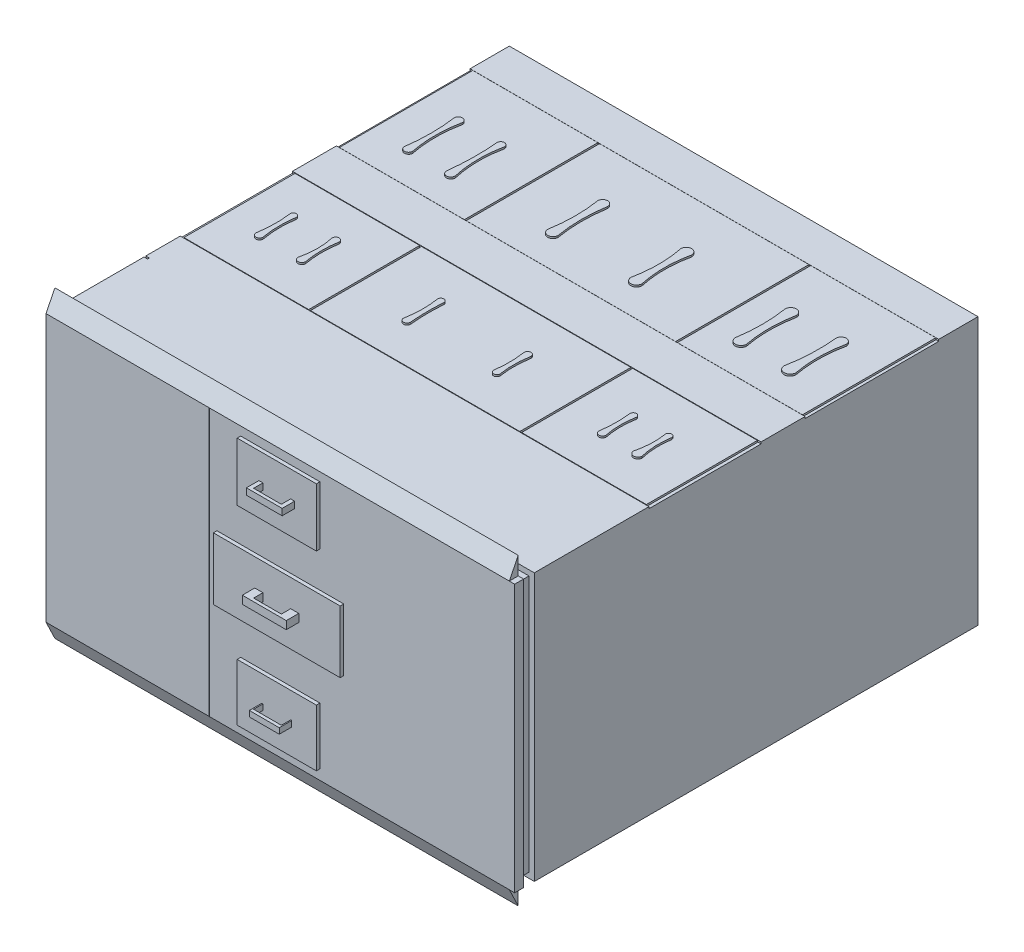
SolidWorks part; units mm, degrees
ref_plane "Alzado" through (0, 0, 0) normal (0, 0, 1) x (1, 0, 0)
ref_plane "Planta" through (0, 0, 0) normal (0, 1, 0) x (1, 0, 0)
ref_plane "Vista lateral" through (0, 0, 0) normal (1, 0, 0) x (0, 0, -1)
sketch "Croquis1" plane through (0, 0, 0) normal (0, 0, 1) x (1, 0, 0)
  line L1 (-1315, -750) -> (1315, -750)
  line L2 (-1315, -750) -> (-1315, 750)
  line L3 (-1315, 750) -> (1315, 750)
  line L4 (1315, -750) -> (1315, 750)
  line L5 (-1315, -750) -> (1315, 750) construction
  line L6 (-1315, 750) -> (1315, -750) construction
  point P0 (0, 0)
  dimension "D1" = 2630
  dimension "D2" = 1500
extrude "Saliente-Extruir1" add sketch "Croquis1" along normal blind 2600
sketch "Croquis2" plane through (-1315, 0, 0) normal (-1, 0, 0) x (0, 0, 1)
  line L0 (2600, 750) -> (0, 750) construction
  line L1 (2000, 600) -> (200, 600)
  line L2 (2000, 600) -> (2000, -100)
  line L3 (2000, -100) -> (200, -100)
  line L4 (200, 600) -> (200, -100)
  line L5 (2000, 600) -> (200, -100) construction
  line L6 (2000, -100) -> (200, 600) construction
  line L7 (0, 750) -> (0, -750) construction
  line L9 (200.2352, 599.7238) -> (1999.7648, 599.7238)
  line L10 (200.2352, 599.7238) -> (200.2352, -99.7238)
  line L11 (200.2352, -99.7238) -> (1999.7648, -99.7238)
  line L12 (1999.7648, 599.7238) -> (1999.7648, -99.7238)
  line L13 (200.2352, 599.7238) -> (1999.7648, -99.7238) construction
  line L14 (200.2352, -99.7238) -> (1999.7648, 599.7238) construction
  point P0 (1100, 250)
  point P9 (1100, 250)
  dimension "D1" = 700
  dimension "D2" = 150
  dimension "D3" = 200
  dimension "D4" = 1800
extrude "Cortar-Extruir1" cut sketch "Croquis2" against normal blind 5
sketch "Croquis3" plane through (-1315, 0, 0) normal (-1, 0, 0) x (0, 0, 1)
  line L0 (1319.1367, 475.2666) -> (1319.1367, 65.2031) construction
  text T0 "KVA" font "Century Gothic" height in points 500
extrude "Saliente-Extruir2" add sketch "Croquis3" along normal blind 10
sketch "Croquis4" plane through (-1315, 0, 0) normal (-1, 0, 0) x (0, 0, 1)
  line L1 (1526.4759, -439.6523) -> (1976.8806, -439.6523)
  line L2 (1526.4759, -439.6523) -> (1526.4759, -764.9446)
  line L3 (1526.4759, -764.9446) -> (1976.8806, -764.9446)
  line L4 (1976.8806, -439.6523) -> (1976.8806, -764.9446)
  line L5 (1526.4759, -439.6523) -> (1976.8806, -764.9446) construction
  line L6 (1526.4759, -764.9446) -> (1976.8806, -439.6523) construction
  line L7 (1526.7662, -439.8619) -> (1976.5903, -439.8619)
  line L8 (1526.7662, -439.8619) -> (1526.7662, -764.7349)
  line L9 (1526.7662, -764.7349) -> (1976.5903, -764.7349)
  line L10 (1976.5903, -439.8619) -> (1976.5903, -764.7349)
  line L11 (1526.7662, -439.8619) -> (1976.5903, -764.7349) construction
  line L12 (1526.7662, -764.7349) -> (1976.5903, -439.8619) construction
  point P0 (1751.6783, -602.2984)
  point P5 (1751.6783, -602.2984)
extrude "Cortar-Extruir2" cut sketch "Croquis4" against normal blind 5
sketch "Croquis5" plane through (-1315, 0, 0) normal (-1, 0, 0) x (0, 0, 1)
  arc A0 (1780.3382, -740.7629) -> (1780.3382, -710.8196) centre (1780.3382, -725.7913) ccw
  arc A1 (1780.3382, -710.8196) -> (1648.3179, -710.8196) centre (1714.3281, 64.5749) cw
  arc A2 (1780.3382, -740.7629) -> (1648.3179, -740.7629) centre (1714.3281, -1706.2715) ccw
  arc A3 (1648.3179, -740.7629) -> (1648.3179, -710.8196) centre (1651.5059, -725.7913) cw
extrude "Saliente-Extruir3" add sketch "Croquis5" along normal blind 130
sketch "Croquis6" plane through (-1315, 0, 0) normal (-1, 0, 0) x (0, 0, 1)
  line L1 (2012.3737, -428.6401) -> (1976.0048, -428.6401)
  line L2 (2012.3737, -428.6401) -> (2012.3737, -783.2373)
  line L3 (2012.3737, -783.2373) -> (1976.0048, -783.2373)
  line L4 (1976.0048, -428.6401) -> (1976.0048, -783.2373)
  line L5 (2012.3737, -428.6401) -> (1976.0048, -783.2373) construction
  line L6 (2012.3737, -783.2373) -> (1976.0048, -428.6401) construction
  point P0 (1994.1892, -605.9387)
extrude "Saliente-Extruir4" add sketch "Croquis6" along normal blind 10
sketch "Croquis7" plane through (-1315, 0, 0) normal (-1, 0, 0) x (0, 0, 1)
  line L0 (2002.8088, -428.6401) -> (2002.8088, -392.561)
  line L1 (2012.3737, -428.6401) -> (1976.0048, -428.6401) construction
  line L2 (2002.8088, -392.561) -> (1981.5113, -392.561)
  line L3 (1981.5113, -392.561) -> (1981.5113, -403.6193)
  line L4 (1981.5113, -428.6401) -> (1981.5113, -403.6193)
  line L6 (2002.8088, -783.2373) -> (2002.8088, -750)
  line L7 (1976.0048, -783.2373) -> (2012.3737, -783.2373) construction
  line L8 (2600, -750) -> (2012.3737, -750) construction
  line L9 (2002.8088, -750) -> (1981.5113, -750)
  line L10 (1981.5113, -750) -> (1981.5113, -783.2373)
  line L11 (1981.5113, -783.2373) -> (2002.8088, -783.2373)
  line L12 (1981.5113, -428.6401) -> (2002.8088, -428.6401)
  line L14 (2002.8088, -783.2373) -> (2002.6702, -783.1658)
extrude "Saliente-Extruir5" add sketch "Croquis7" along normal blind 10
sketch "Croquis8" plane through (-1315, 0, 0) normal (-1, 0, 0) x (0, 0, 1)
  arc A0 (1260.1406, -2.5348) -> (1259.4668, 20.6791) centre (1260.4672, 9.0914) ccw
  arc A1 (1260.1406, -2.5348) -> (1056.2677, -15.1971) centre (1241.402, -1348.4194) ccw
  arc A2 (1259.4668, 20.6791) -> (1056.2677, 37.0054) centre (1224.0968, 853.1435) cw
  arc A3 (1056.2677, 37.0054) -> (1056.2677, -15.1971) centre (1056.2677, 10.9041) ccw
extrude "Saliente-Extruir6" add sketch "Croquis8" along normal blind 10
sketch "Croquis9" plane through (-1315, 0, 0) normal (-1, 0, 0) x (0, 0, 1)
  line L1 (1985.9589, 369.0843) -> (1802.2688, 369.0843)
  line L2 (1985.9589, 369.0843) -> (1985.9589, 242.2506)
  line L3 (1985.9589, 242.2506) -> (1802.2688, 242.2506)
  line L4 (1802.2688, 369.0843) -> (1802.2688, 242.2506)
  line L5 (1985.9589, 369.0843) -> (1802.2688, 242.2506) construction
  line L6 (1985.9589, 242.2506) -> (1802.2688, 369.0843) construction
  line L7 (1803.3097, 367.3482) -> (1984.918, 367.3482)
  line L8 (1803.3097, 367.3482) -> (1803.3097, 243.9867)
  line L9 (1803.3097, 243.9867) -> (1984.918, 243.9867)
  line L10 (1984.918, 367.3482) -> (1984.918, 243.9867)
  line L11 (1803.3097, 367.3482) -> (1984.918, 243.9867) construction
  line L12 (1803.3097, 243.9867) -> (1984.918, 367.3482) construction
  point P0 (1894.1138, 305.6675)
  point P5 (1894.1138, 305.6675)
extrude "Cortar-Extruir3" cut sketch "Croquis9" against normal blind 5
sketch "Croquis10" plane through (-1315, 0, 0) normal (-1, 0, 0) x (0, 0, 1)
  line L1 (2600, 750) -> (0, 750) construction
  line L2 (2050, 750) -> (2050, -750)
  line L3 (2600, -750) -> (2012.3737, -750) construction
  line L4 (2050, -750) -> (2040, -750)
  line L5 (2040, -750) -> (2040, 750)
  line L6 (2040, 750) -> (2050, 750)
  dimension "D2" = 10
extrude "Cortar-Extruir4" cut sketch "Croquis10" against normal blind 20
sketch "Croquis11" plane through (0, -750, 0) normal (0, -1, 0) x (1, 0, 0)
  line L0 (-1315, 2600) -> (-1315, 2050)
  line L1 (-1315, 2600) -> (-1315, 2050) construction
  line L2 (-1315, 2050) -> (1315, 2050)
  line L3 (1315, 2600) -> (1315, 0) construction
  line L4 (1315, 2050) -> (1309.7781, 2050)
  line L5 (1309.7781, 2050) -> (1309.7781, 2040)
  line L6 (1309.7781, 2040) -> (-1341.4375, 2040)
  line L7 (-1341.4375, 2040) -> (-1341.4375, 2050)
  line L8 (-1341.4375, 2050) -> (-1315, 2050)
  line M6 (-1295, 2050) -> (-1295, 2040)
  line M14 (1315, 0) -> (1315, 2600)
  dimension "D1" = 550
  dimension "D2" = 10
extrude "Cortar-Extruir5" cut sketch "Croquis11" against normal blind 20 contours L6 L2 M14 M6
sketch "Croquis14" plane through (-1315, 0, 0) normal (-1, 0, 0) x (0, 0, 1)
  line L0 (2370.2413, 341.8092) -> (2353.0065, 332.4084)
  line L1 (2353.0065, 332.4084) -> (2310.7029, 360.6108)
  line L2 (2310.7029, 360.6108) -> (2291.9013, 332.4084)
  line L3 (2291.9013, 332.4084) -> (2249.5977, 360.6108)
  line L4 (2249.5977, 360.6108) -> (2233.9297, 337.1088)
  line L5 (2233.9297, 337.1088) -> (2214.5255, 308.0025)
  line L6 (2214.5255, 308.0025) -> (2241.7637, 313.4502)
  line L10 (2241.7637, 313.4502) -> (2241.7637, 294.0219)
  line L11 (2241.7637, 294.0219) -> (2282.5005, 313.4502)
  line L12 (2282.5005, 313.4502) -> (2259.9673, 274.409)
  line L13 (2259.9673, 274.409) -> (2313.8766, 308.0025)
  line L14 (2313.8766, 308.0025) -> (2305.6973, 282.9601)
  line L15 (2305.6973, 282.9601) -> (2386.4898, 323.9697)
  line L16 (2386.4898, 323.9697) -> (2370.2413, 341.8092)
  point P0 (2276.2984, 324.5929)
extrude "Saliente-Extruir7" add sketch "Croquis14" along normal blind 20
sketch "Croquis15" plane through (-1315, 0, 0) normal (-1, 0, 0) x (0, 0, 1)
  line L1 (2440.381, 319.4871) -> (2183.8004, 467.6239)
  line L2 (2183.8004, 467.6239) -> (2183.8004, 171.3502)
  line L3 (2183.8004, 171.3502) -> (2440.381, 319.4871)
  circle A0 centre (2269.3272, 319.4871) radius 85.5269 construction
extrude "Saliente-Extruir8" add sketch "Croquis15" along normal blind 10
sketch "Croquis16" plane through (-1315, 0, 0) normal (-1, 0, 0) x (0, 0, 1)
  line L1 (2600, 750) -> (2050, 750) construction
  line L2 (2550, 750) -> (2490, 750)
  line L3 (2490, 750) -> (2490, -750)
  line L4 (2600, -750) -> (2050, -750) construction
  line L5 (2490, -750) -> (2550, -750)
  line L6 (2550, -750) -> (2550, 750)
  dimension "D2" = 60
extrude "Cortar-Extruir8" cut sketch "Croquis16" against normal blind 30
sketch "Croquis17" plane through (0, -750, 0) normal (0, -1, 0) x (1, 0, 0)
  line L0 (1388.3737, 2490) -> (-1371.915, 2490)
  line L1 (1388.3737, 2550) -> (1388.3737, 2490)
  line L2 (-1371.915, 2490) -> (-1371.915, 2550)
  line L3 (-1371.915, 2550) -> (1388.3737, 2550)
  dimension "D1" = 60
extrude "Cortar-Extruir9" cut sketch "Croquis17" against normal blind 30
sketch "Croquis18" plane through (1315, 0, 0) normal (1, 0, 0) x (0, 0, -1)
  line L0 (-2550, -917.8528) -> (-2550, 835.2908)
  line L3 (-2550, 835.2908) -> (-2490, 835.2908)
  line L4 (-2490, 835.2908) -> (-2490, -917.8528)
  line L5 (-2490, -917.8528) -> (-2550, -917.8528)
  dimension "D1" = 60
extrude "Cortar-Extruir10" cut sketch "Croquis18" against normal blind 30
sketch "Croquis19" plane through (0, 750, 0) normal (0, 1, 0) x (1, 0, 0)
  line L1 (1315, -2550) -> (-1411.6841, -2550)
  line L2 (-1411.6841, -2550) -> (-1411.6841, -2490)
  line L3 (-1411.6841, -2490) -> (1341.505, -2490)
  line L4 (1341.505, -2490) -> (1341.505, -2550)
  line L5 (1341.505, -2550) -> (1315, -2550)
extrude "Cortar-Extruir11" cut sketch "Croquis19" against normal blind 30
sketch "Croquis20" plane through (-1315, 0, 0) normal (-1, 0, 0) x (0, 0, 1)
  line L0 (2550, -750) -> (2550, -853.7683)
  line L1 (2550, -853.7683) -> (2600, -750)
  line L2 (2550, 750) -> (2550, 850.1214)
  line L3 (2550, 850.1214) -> (2600, 750)
  line L4 (2600, 750) -> (2550, 750)
  line L5 (2550, -750) -> (2600, -750)
extrude "Saliente-Extruir9" add sketch "Croquis20" against normal blind 2600
sketch "Croquis28" plane through (0, 750, 0) normal (0, 1, 0) x (1, 0, 0)
  line L0 (1315, -1846.4807) -> (-1315, -1846.4807)
  line L1 (1315, -2490) -> (1315, 0) construction
  line L2 (-1315, -2040) -> (-1315, 0) construction
  line L3 (1315, -1846.4807) -> (1315, -1217.335)
  line L4 (1315, -1217.335) -> (-1315, -1217.335)
  line L5 (-1315, -1217.335) -> (-1315, -1846.4807)
  line L7 (1297.5126, -1220.2763) -> (-1297.5126, -1220.2763)
  line L8 (1297.5126, -1220.2763) -> (1297.5126, -1843.5394)
  line L9 (1297.5126, -1843.5394) -> (-1297.5126, -1843.5394)
  line L10 (-1297.5126, -1220.2763) -> (-1297.5126, -1843.5394)
  line L11 (1297.5126, -1220.2763) -> (-1297.5126, -1843.5394) construction
  line L12 (1297.5126, -1843.5394) -> (-1297.5126, -1220.2763) construction
  point P6 (0, -1531.9079)
extrude "Cortar-Extruir18" cut sketch "Croquis28" against normal blind 10
sketch "Croquis29" plane through (0, 750, 0) normal (0, 1, 0) x (1, 0, 0)
  line L0 (-597.5126, -1531.9079) -> (-597.5126, -1843.5394)
  line L4 (597.5126, -1843.5394) -> (597.5126, -1220.2763)
  line L7 (597.5126, -1220.2763) -> (587.5126, -1220.2763)
  line L8 (1297.5126, -1220.2763) -> (-1297.5126, -1220.2763) construction
  line L9 (1297.5126, -1220.2763) -> (-1297.5126, -1220.2763) construction
  line L10 (587.5126, -1220.2763) -> (587.5126, -1843.5394)
  line L11 (-1297.5126, -1843.5394) -> (1297.5126, -1843.5394) construction
  line L12 (587.5126, -1843.5394) -> (597.5126, -1843.5394)
  line L13 (-597.5126, -1843.5394) -> (-587.5126, -1843.5394)
  line L14 (-587.5126, -1843.5394) -> (-587.5126, -1220.2763)
  line L15 (-587.5126, -1220.2763) -> (-597.5126, -1220.2763)
  line L16 (-597.5126, -1220.2763) -> (-597.5126, -1531.9079)
  dimension "D1" = 10
  dimension "D3" = 10
extrude "Cortar-Extruir19" cut sketch "Croquis29" against normal blind 10
sketch "Croquis30" plane through (0, 750, 0) normal (0, 1, 0) x (1, 0, 0)
  line L0 (1315, -220.2763) -> (1315, -970.2763)
  line L1 (1315, -1217.335) -> (1315, 0) construction
  line L2 (1297.5126, -1220.2763) -> (597.5126, -1220.2763) construction
  line L3 (1315, -970.2763) -> (1003.7101, -970.2763)
  line L4 (-1315, -970.2763) -> (-1315, -220.2763)
  line L5 (-1315, -1217.335) -> (-1315, 0) construction
  line L6 (-1315, -220.2763) -> (1315, -220.2763)
  line L8 (-1315, -970.2763) -> (1003.7101, -970.2763)
  line L9 (1299.2276, -221.062) -> (-1299.2276, -221.062)
  line L10 (1299.2276, -221.062) -> (1299.2276, -969.4906)
  line L11 (1299.2276, -969.4906) -> (-1299.2276, -969.4906)
  line L12 (-1299.2276, -221.062) -> (-1299.2276, -969.4906)
  line L13 (1299.2276, -221.062) -> (-1299.2276, -969.4906) construction
  line L14 (1299.2276, -969.4906) -> (-1299.2276, -221.062) construction
  point P11 (0, -595.2763)
  dimension "D1" = 750
  dimension "D2" = 250
extrude "Cortar-Extruir20" cut sketch "Croquis30" against normal blind 10
sketch "Croquis31" plane through (0, 750, 0) normal (0, 1, 0) x (1, 0, 0)
  line L0 (587.5126, -969.4906) -> (587.5126, -221.062)
  line L1 (-1299.2276, -969.4906) -> (1299.2276, -969.4906) construction
  line L2 (1299.2276, -221.062) -> (-1299.2276, -221.062) construction
  line L3 (587.5126, -221.062) -> (597.5126, -221.062)
  line L4 (597.5126, -221.062) -> (597.5126, -969.4906)
  line L5 (-1299.2276, -969.4906) -> (1299.2276, -969.4906) construction
  line L6 (597.5126, -969.4906) -> (587.5126, -969.4906)
  line L7 (-587.5126, -969.4906) -> (-587.5126, -221.062)
  line L8 (-587.5126, -221.062) -> (-597.5126, -221.062)
  line L9 (1299.2276, -221.062) -> (-1299.2276, -221.062) construction
  line L10 (-597.5126, -221.062) -> (-597.5126, -969.4906)
  line L11 (-597.5126, -969.4906) -> (-587.5126, -969.4906)
  dimension "D1" = 10
  dimension "D2" = 10
extrude "Cortar-Extruir21" cut sketch "Croquis31" against normal blind 10
sketch "Croquis32" plane through (0, 750, 0) normal (0, 1, 0) x (1, 0, 0)
  arc A0 (226.1322, -1629.2485) -> (262.3012, -1629.2485) centre (244.2167, -1629.2485) ccw
  arc A1 (-279.5439, -1629.2485) -> (-240.2668, -1629.2485) centre (-259.9054, -1629.2485) ccw
  arc A2 (-242.3401, -1439.544) -> (-277.4706, -1439.544) centre (-259.9054, -1439.544) ccw
  arc A3 (263.5384, -1457.1092) -> (224.8949, -1457.1092) centre (244.2167, -1457.1092) ccw
  arc A4 (263.5384, -1457.1092) -> (262.3012, -1629.2485) centre (777.7885, -1546.8795) ccw
  arc A5 (224.8949, -1457.1092) -> (226.1322, -1629.2485) centre (-345.2759, -1547.2814) cw
  arc A6 (-240.2668, -1629.2485) -> (-242.3401, -1439.544) centre (860.3622, -1522.3561) cw
  arc A7 (-279.5439, -1629.2485) -> (-277.4706, -1439.544) centre (-830.4924, -1528.3636) ccw
  arc A8 (-871.2729, -1629.2485) -> (-828.94, -1629.2485) centre (-850.1064, -1629.2485) ccw
  arc A9 (-830.4492, -1439.544) -> (-869.7637, -1439.544) centre (-850.1064, -1439.544) ccw
  arc A10 (-1071.1318, -1444.6629) -> (-1104.8565, -1444.2543) centre (-1087.9346, -1439.544) ccw
  arc A11 (-1108.2578, -1629.2485) -> (-1067.6114, -1629.2485) centre (-1087.9346, -1629.2485) ccw
  arc A12 (816.9987, -1629.2485) -> (857.2101, -1629.2485) centre (837.1044, -1629.2485) ccw
  arc A13 (1011.5094, -1629.2485) -> (1060.1358, -1629.2485) centre (1035.8226, -1629.2485) ccw
  arc A14 (1053.2252, -1457.1092) -> (1018.42, -1457.1092) centre (1035.8226, -1457.1092) ccw
  arc A15 (855.1846, -1457.1092) -> (819.0242, -1457.1092) centre (837.1044, -1457.1092) ccw
  arc A16 (1053.2252, -1457.1092) -> (1060.1358, -1629.2485) centre (1486.1051, -1525.9395) ccw
  arc A17 (1018.42, -1457.1092) -> (1011.5094, -1629.2485) centre (598.9406, -1526.4774) cw
  arc A18 (857.2101, -1629.2485) -> (855.1846, -1457.1092) centre (1297.0728, -1537.9912) cw
  arc A19 (819.0242, -1457.1092) -> (816.9987, -1629.2485) centre (191.1998, -1535.8034) cw
  arc A20 (-828.94, -1629.2485) -> (-830.4492, -1439.544) centre (-292.9516, -1530.1262) cw
  arc A21 (-871.2729, -1629.2485) -> (-869.7637, -1439.544) centre (-1280.813, -1531.1322) ccw
  arc A22 (-1067.6114, -1629.2485) -> (-1071.1318, -1444.6629) centre (-506.0515, -1526.212) cw
  arc A23 (-1108.2578, -1629.2485) -> (-1104.8565, -1444.2543) centre (-1717.4157, -1525.52) ccw
  arc A24 (-1110.9413, -792.7224) -> (-1064.9279, -792.7224) centre (-1087.9346, -792.7224) ccw
  arc A25 (-1065.0376, -513.457) -> (-1110.8317, -513.457) centre (-1087.9346, -513.457) ccw
  arc A26 (-874.7473, -792.7224) -> (-825.4655, -792.7224) centre (-850.1064, -792.7224) ccw
  arc A27 (-829.2909, -513.457) -> (-870.9219, -513.457) centre (-850.1064, -513.457) ccw
  arc A28 (-306.7551, -792.7224) -> (-248.1861, -792.7224) centre (-277.4706, -792.7224) ccw
  arc A29 (-249.5291, -513.457) -> (-305.412, -513.457) centre (-277.4706, -513.457) ccw
  arc A30 (160.1374, -792.7224) -> (222.2622, -792.7224) centre (191.1998, -792.7224) ccw
  arc A31 (221.5603, -513.457) -> (160.8393, -513.457) centre (191.1998, -513.457) ccw
  arc A32 (746.2642, -792.7224) -> (809.3128, -792.7224) centre (777.7885, -792.7224) ccw
  arc A33 (1019.7171, -792.7224) -> (1086.7333, -792.7224) centre (1053.2252, -792.7224) ccw
  arc A34 (1089.2252, -513.457) -> (1031.0464, -513.457) centre (1060.1358, -513.457) ccw
  arc A35 (809.4047, -513.457) -> (746.1723, -513.457) centre (777.7885, -513.457) ccw
  arc A36 (1089.2252, -513.457) -> (1086.7333, -792.7224) centre (1783.923, -659.2997) ccw
  arc A37 (1019.7171, -792.7224) -> (1031.0464, -513.457) centre (85.1894, -614.9479) ccw
  arc A38 (809.3128, -792.7224) -> (809.4047, -513.457) centre (1521.75, -653.324) cw
  arc A39 (746.2642, -792.7224) -> (746.1723, -513.457) centre (-132.8526, -653.3789) ccw
  arc A40 (222.2622, -792.7224) -> (221.5603, -513.457) centre (859.9671, -651.4861) cw
  arc A41 (160.1374, -792.7224) -> (160.8393, -513.457) centre (-524.7998, -651.3674) ccw
  arc A42 (-248.1861, -792.7224) -> (-249.5291, -513.457) centre (589.4791, -649.0578) cw
  arc A43 (-306.7551, -792.7224) -> (-305.412, -513.457) centre (-1147.1072, -649.0449) ccw
  arc A44 (-825.4655, -792.7224) -> (-829.2909, -513.457) centre (-190.2916, -644.3628) cw
  arc A45 (-874.7473, -792.7224) -> (-870.9219, -513.457) centre (-2154.9057, -635.5278) ccw
  arc A46 (-1064.9279, -792.7224) -> (-1065.0376, -513.457) centre (-368.6066, -652.8163) cw
  arc A47 (-1110.9413, -792.7224) -> (-1110.8317, -513.457) centre (-2113.3391, -652.6961) ccw
extrude "Saliente-Extruir11" add sketch "Croquis32" along normal blind 10
sketch "Croquis34" plane through (-1315, 0, 0) normal (-1, 0, 0) x (0, 0, 1)
  line L1 (1526.7662, -439.8619) -> (1976.0048, -439.8619)
  line L2 (1526.7662, -439.8619) -> (1526.7662, -750)
  line L3 (1526.7662, -750) -> (1976.0048, -750)
  line L4 (1976.0048, -439.8619) -> (1976.0048, -750)
  line L5 (1526.7662, -439.8619) -> (1976.0048, -750) construction
  line L6 (1526.7662, -750) -> (1976.0048, -439.8619) construction
  point P0 (1751.3855, -594.931)
extrude "Saliente-Extruir14" add sketch "Croquis34" along normal blind 120
sketch "Croquis35" plane through (0, 0, 2600) normal (0, 0, 1) x (1, 0, 0)
  line L1 (-400, 0) -> (-400, -56.3996)
  line L2 (397.6045, 797.864) -> (-397.6045, 797.864)
  line L3 (400, 0) -> (400, -750)
  line L4 (-1315, -750) -> (1285, -750) construction
  line L5 (400, -750) -> (-400, -750)
  line L6 (-400, -750) -> (-400, 750)
  line L7 (1285, 750) -> (-1315, 750) construction
  line L8 (-400, 750) -> (400, 750)
  line L9 (400, 750) -> (400, 0)
  line L10 (397.6045, 797.864) -> (397.6045, -797.864)
  line L11 (397.6045, -797.864) -> (-397.6045, -797.864)
  line L12 (-397.6045, 797.864) -> (-397.6045, -797.864)
  line L13 (397.6045, 797.864) -> (-397.6045, -797.864) construction
  line L14 (397.6045, -797.864) -> (-397.6045, 797.864) construction
  point P0 (0, 0)
  line M4 (1285, 750) -> (-1315, 750)
  line M6 (-1315, -750) -> (1285, -750)
extrude "Cortar-Extruir22" cut sketch "Croquis35" against normal blind 10 contours L9 L6 L1 L3 L12 L2 L10 L11 M4 M6
sketch "Croquis36" plane through (0, 0, 2600) normal (0, 0, 1) x (1, 0, 0)
  line L1 (355.8129, 174.2593) -> (-355.8129, 174.2593)
  line L2 (355.8129, 174.2593) -> (355.8129, -174.2593)
  line L3 (355.8129, -174.2593) -> (-355.8129, -174.2593)
  line L4 (-355.8129, 174.2593) -> (-355.8129, -174.2593)
  line L5 (355.8129, 174.2593) -> (-355.8129, -174.2593) construction
  line L6 (355.8129, -174.2593) -> (-355.8129, 174.2593) construction
  line L7 (222.0716, -693.7525) -> (-222.0716, -693.7525)
  line L8 (222.0716, -693.7525) -> (222.0716, -374.2593)
  line L9 (222.0716, -374.2593) -> (-222.0716, -374.2593)
  line L10 (-222.0716, -693.7525) -> (-222.0716, -374.2593)
  line L11 (222.0716, -693.7525) -> (-222.0716, -374.2593) construction
  line L12 (222.0716, -374.2593) -> (-222.0716, -693.7525) construction
  line L13 (222.0716, 701.1826) -> (-222.0716, 701.1826)
  line L14 (222.0716, 701.1826) -> (222.0716, 374.2593)
  line L15 (222.0716, 374.2593) -> (-222.0716, 374.2593)
  line L16 (-222.0716, 701.1826) -> (-222.0716, 374.2593)
  line L17 (222.0716, 701.1826) -> (-222.0716, 374.2593) construction
  line L18 (222.0716, 374.2593) -> (-222.0716, 701.1826) construction
  point P0 (0, 0)
  point P6 (0, -534.0059)
  point P11 (0, 537.7209)
  dimension "D1" = 200
  dimension "D2" = 200
extrude "Saliente-Extruir15" add sketch "Croquis36" along normal blind 20
sketch "Croquis37" plane through (0, 0, 2620) normal (0, 0, 1) x (1, 0, 0)
  line L1 (83.9128, -518.1192) -> (-83.9128, -518.1192)
  line L2 (83.9128, -518.1192) -> (83.9128, -549.8927)
  line L3 (83.9128, -549.8927) -> (-83.9128, -549.8927)
  line L4 (-83.9128, -518.1192) -> (-83.9128, -549.8927)
  line L5 (83.9128, -518.1192) -> (-83.9128, -549.8927) construction
  line L6 (83.9128, -549.8927) -> (-83.9128, -518.1192) construction
  line L7 (123.3669, -22.2151) -> (-123.3669, -22.2151)
  line L8 (123.3669, -22.2151) -> (123.3669, 22.2151)
  line L9 (123.3669, 22.2151) -> (-123.3669, 22.2151)
  line L10 (-123.3669, -22.2151) -> (-123.3669, 22.2151)
  line L11 (123.3669, -22.2151) -> (-123.3669, 22.2151) construction
  line L12 (123.3669, 22.2151) -> (-123.3669, -22.2151) construction
  line L13 (100.088, 519.6226) -> (-100.088, 519.6226)
  line L14 (100.088, 519.6226) -> (100.088, 555.8193)
  line L15 (100.088, 555.8193) -> (-100.088, 555.8193)
  line L16 (-100.088, 519.6226) -> (-100.088, 555.8193)
  line L17 (100.088, 519.6226) -> (-100.088, 555.8193) construction
  line L18 (100.088, 555.8193) -> (-100.088, 519.6226) construction
  point P0 (0, -534.0059)
  point P5 (0, 0)
  point P11 (0, 537.7209)
extrude "Saliente-Extruir16" add sketch "Croquis37" along normal blind 70
sketch "Croquis38" plane through (0, 555.8193, 0) normal (0, 1, 0) x (1, 0, 0)
  line L0 (78.0008, -2620) -> (78.0008, -2672.2625)
  line L1 (100.088, -2620) -> (-100.088, -2620) construction
  line L2 (78.0008, -2672.2625) -> (-77.6387, -2672.2625)
  line L3 (-77.6387, -2672.2625) -> (-77.6387, -2620)
  line L4 (-77.6387, -2620) -> (78.0008, -2620)
extrude "Cortar-Extruir23" cut sketch "Croquis38" against normal up to surface (1105.712 mm away) up to face at (0, -549.8927, 2655)
